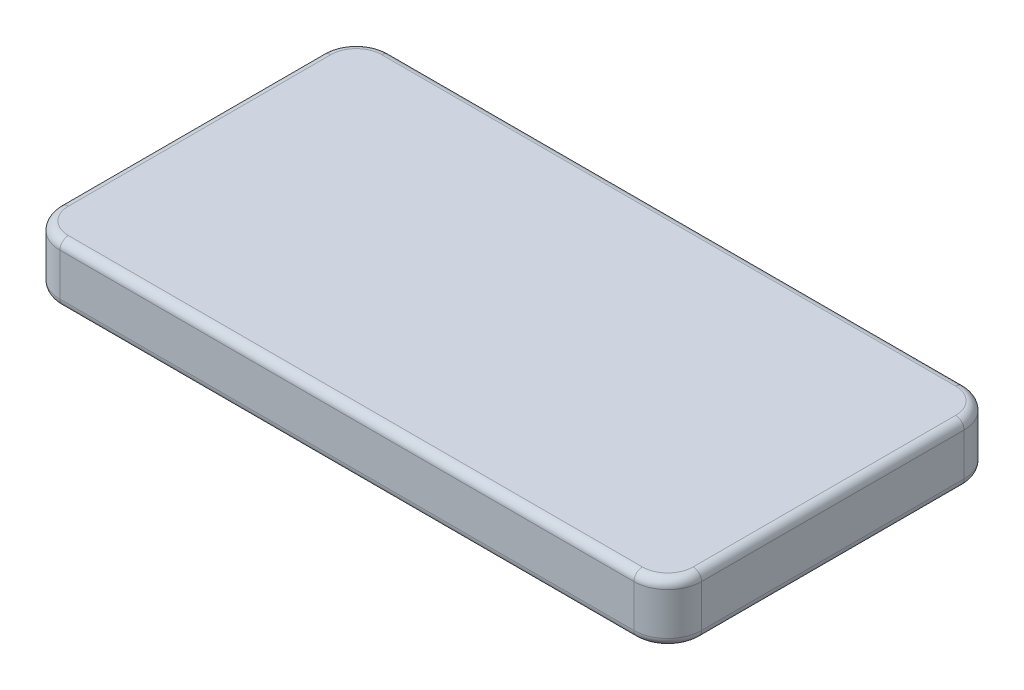
SolidWorks part; units mm, degrees
ref_plane "Front Plane" through (0, 0, 0) normal (0, 0, 1) x (1, 0, 0)
ref_plane "Top Plane" through (0, 0, 0) normal (0, 1, 0) x (1, 0, 0)
ref_plane "Right Plane" through (0, 0, 0) normal (1, 0, 0) x (0, 0, -1)
sketch "Sketch1" plane through (0, 0, 0) normal (0, 1, 0) x (1, 0, 0)
  line L1 (-48.133, -24.765) -> (48.133, -24.765)
  line L2 (-48.133, -24.765) -> (-48.133, 24.765)
  line L3 (-48.133, 24.765) -> (48.133, 24.765)
  line L4 (48.133, -24.765) -> (48.133, 24.765)
  line L5 (-48.133, -24.765) -> (48.133, 24.765) construction
  line L6 (-48.133, 24.765) -> (48.133, -24.765) construction
  point P0 (0, 0)
  dimension "D1" = 96.266
  dimension "D2" = 49.53
extrude "Boss-Extrude1" add sketch "Sketch1" along normal mid plane 8.89
fillet "Fillet1" radius 5.08 4 edges at (-48.133, 0, -24.765) (-48.133, 0, 24.765) (48.133, 0, -24.765) (48.133, 0, 24.765)
fillet "Fillet2" radius 1.27 16 edges at (-46.6451, -4.445, 23.2771) (0, -4.445, 24.765) (46.6451, -4.445, 23.2771) (48.133, -4.445, 0) (46.6451, -4.445, -23.2771) (0, -4.445, -24.765) (-46.6451, -4.445, -23.2771) (-48.133, -4.445, 0) (46.6451, 4.445, -23.2771) (48.133, 4.445, 0) (46.6451, 4.445, 23.2771) (0, 4.445, 24.765) (-46.6451, 4.445, 23.2771) (-48.133, 4.445, 0) (-46.6451, 4.445, -23.2771) (0, 4.445, -24.765)
